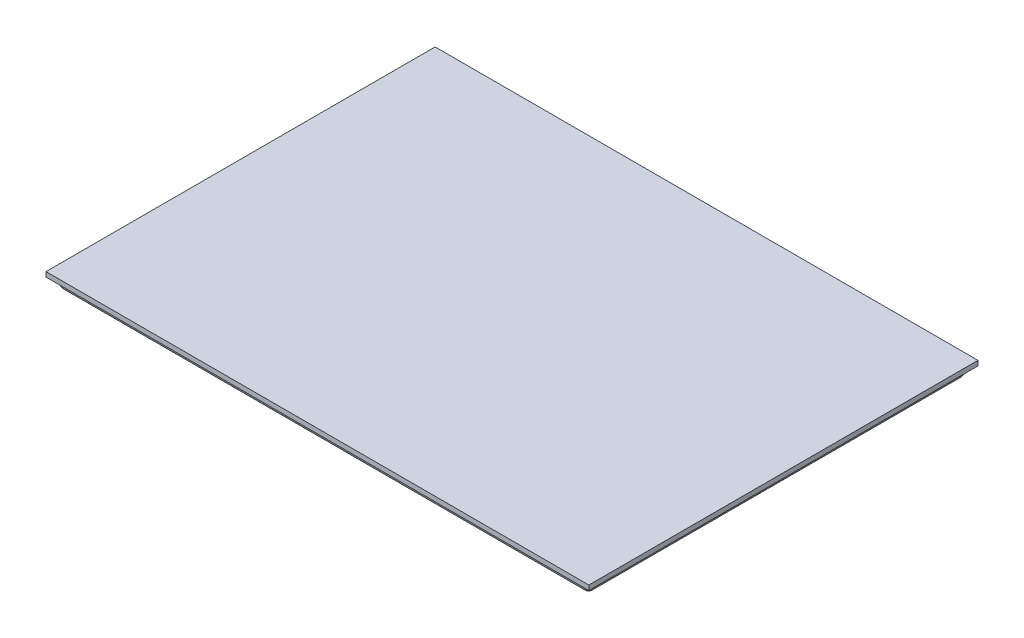
SolidWorks part; units mm, degrees
ref_plane "Front Plane" through (0, 0, 0) normal (0, 0, 1) x (1, 0, 0)
ref_plane "Top Plane" through (0, 0, 0) normal (0, 1, 0) x (1, 0, 0)
ref_plane "Right Plane" through (0, 0, 0) normal (1, 0, 0) x (0, 0, -1)
sketch "Sketch1" plane through (0, 0, 0) normal (0, 1, 0) x (1, 0, 0)
  line L1 (-56.5, -40.5) -> (56.5, -40.5)
  line L2 (-56.5, -40.5) -> (-56.5, 40.5)
  line L3 (-56.5, 40.5) -> (56.5, 40.5)
  line L4 (56.5, -40.5) -> (56.5, 40.5)
  line L5 (-56.5, -40.5) -> (56.5, 40.5) construction
  line L6 (-56.5, 40.5) -> (56.5, -40.5) construction
  point P0 (0, 0)
  dimension "D1" = 113
  dimension "D2" = 81
extrude "Boss-Extrude1" add sketch "Sketch1" along normal blind 1
sketch "Sketch2" plane through (0, 0, 0) normal (0, -1, 0) x (1, 0, 0)
  line L0 (-56.5, 40.5) -> (56.5, 40.5) construction
  line L1 (-55.35, -39.4) -> (55.35, -39.4)
  line L2 (-55.35, -39.4) -> (-55.35, 39.4)
  line L3 (-55.35, 39.4) -> (55.35, 39.4)
  line L4 (55.35, -39.4) -> (55.35, 39.4)
  line L5 (-55.35, -39.4) -> (55.35, 39.4) construction
  line L6 (-55.35, 39.4) -> (55.35, -39.4) construction
  line L7 (56.5, 40.5) -> (56.5, -40.5) construction
  point P0 (0, 0)
  dimension "1.15" = 1.1
  dimension "D2" = 1.15
extrude "Boss-Extrude2" add sketch "Sketch2" along normal blind 2
fillet "Fillet3" radius 1 8 edges at (0, -2, -39.4) (-55.35, -2, 0) (0, -2, 39.4) (55.35, -2, 0) (-55.35, -1, -39.4) (-55.35, -1, 39.4) (55.35, -1, 39.4) (55.35, -1, -39.4)
equation "\"BoxLength\"= 113"
equation "\"BoxWidth\"= 81"
equation "\"D1@Sketch1\"=\"BoxLength\""
equation "\"D2@Sketch1\"=\"BoxWidth\""
